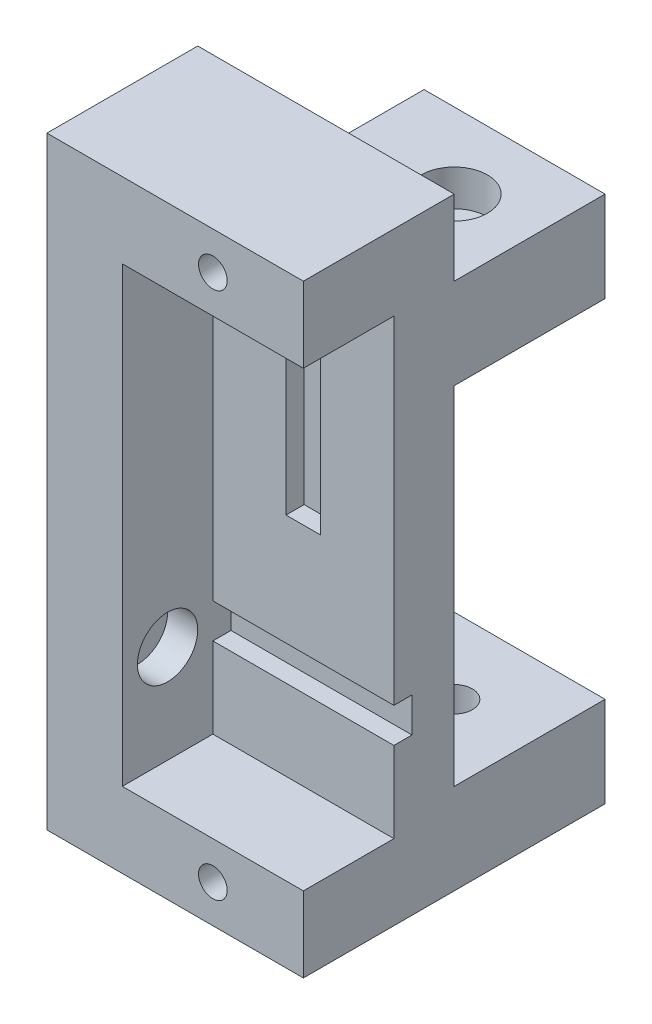
SolidWorks part; units mm, degrees
ref_plane "Plan de face" through (0, 0, 0) normal (0, 0, 1) x (1, 0, 0)
ref_plane "Plan de dessus" through (0, 0, 0) normal (0, 1, 0) x (1, 0, 0)
ref_plane "Plan de droite" through (0, 0, 0) normal (1, 0, 0) x (0, 0, -1)
sketch "Esquisse1" plane through (0, 0, 0) normal (0, 0, 1) x (1, 0, 0)
  line L0 (10, 9.5) -> (10, -9.5) construction
  line L1 (-2, -17.5) -> (10, -17.5)
  line L2 (-2, -17.5) -> (-2, 22.5)
  line L3 (-2, 22.5) -> (10, 22.5)
  line L4 (10, -17.5) -> (10, 22.5)
  line L7 (18, 11.5) -> (0, 11.5) construction
  line L8 (18, -11.5) -> (0, -11.5) construction
  line L9 (0, 11.5) -> (0, -11.5) construction
  dimension "D1" = 11
  dimension "D2" = 6
  dimension "D3" = 2
extrude "Boss.-Extru.1" add sketch "Esquisse1" along normal blind 4
sketch "Esquisse2" plane through (0, 0, 0) normal (0, 0, -1) x (-1, 0, 0)
  line L0 (-10, -17.5) -> (-10, 22.5) construction
  line L1 (2, -17.5) -> (-10, -17.5)
  line L2 (2, -17.5) -> (2, -11.5)
  line L3 (2, -11.5) -> (-10, -11.5)
  line L4 (-10, -17.5) -> (-10, -11.5)
  line L5 (-10, -11.5) -> (0, -11.5) construction
extrude "Boss.-Extru.2" add sketch "Esquisse2" along normal blind 10
mirror "Symétrie1" about plane through (0, 0, 0) normal (0, 1, 0) of "Boss.-Extru.2"
sketch "Esquisse4" plane through (0, 0, 4) normal (0, 0, 1) x (1, 0, 0)
  line L0 (10, -17.5) -> (10, 22.5) construction
  line L1 (-2, 22.5) -> (10, 22.5)
  line L2 (-2, 22.5) -> (-2, 17.5)
  line L3 (-2, 17.5) -> (10, 17.5)
  line L4 (10, 22.5) -> (10, 17.5)
  line L10 (0, 0) -> (3.8663, 0) construction
  line L16 (-2, -17.5) -> (10, -17.5)
  line L17 (-2, -17.5) -> (-2, -12.5)
  line L18 (-2, -12.5) -> (10, -12.5)
  line L19 (10, -17.5) -> (10, -12.5)
  dimension "D1" = 5
extrude "Boss.-Extru.3" add sketch "Esquisse4" along normal blind 6
sketch "Esquisse5" plane through (0, 0, 10) normal (0, 0, 1) x (1, 0, 0)
  line L0 (0, 0) -> (2.5887, 0) construction
  line L1 (-2, -12.5) -> (-2, -17.5) construction
  line L2 (-2, -17.5) -> (10, -17.5) construction
  line L3 (-2, 22.5) -> (-2, 17.5) construction
  line L4 (-2, 17.5) -> (10, 17.5) construction
  circle A0 centre (4, -15) radius 0.95
  circle A1 centre (4, 20) radius 0.95
  point P8 (-2, -15)
  point P11 (4, -17.5)
  point P18 (-2, 20)
  point P21 (4, 17.5)
  dimension "D1" = 1.9
extrude "Enlèv. mat.-Extru.2" cut sketch "Esquisse5" against normal blind 5
sketch "Esquisse6" plane through (-2, 0, 0) normal (-1, 0, 0) x (0, 0, 1)
  line L0 (10, -17.5) -> (-10, -17.5) construction
  line L1 (10, 22.5) -> (0, 22.5)
  line L2 (10, 22.5) -> (10, -17.5)
  line L3 (10, -17.5) -> (0, -17.5)
  line L4 (0, 22.5) -> (0, -17.5)
extrude "Boss.-Extru.4" add sketch "Esquisse6" along normal blind 5
sketch "Esquisse7" plane through (-2, 0, 0) normal (1, 0, 0) x (0, 0, -1)
  line L0 (-4, 17.5) -> (-4, -12.5) construction
  line L2 (-0.66, -6) -> (0.66, -6) construction
  circle A0 centre (-7, -6) radius 2
  point P4 (0, 0)
  point P7 (0, 0)
  point P9 (0, 0)
  point P10 (0, 0)
  dimension "D3" = 4
  dimension "D1" = 3
extrude "Enlèv. mat.-Extru.3" cut sketch "Esquisse7" against normal blind 2
sketch "Esquisse10" plane through (0, -17.5, 0) normal (0, -1, 0) x (-1, 0, 0)
  line L0 (-10, 10) -> (2, 10) construction
  line L1 (-10, -10) -> (-10, 10) construction
  point P0 (-5, 5)
  dimension "D1" = 5
  dimension "D2" = 5
hole_wizard "Chambrage pour vis à six pans creux M21" positions "Esquisse10" profile "Esquisse9" counterbore size "M2" standard "ISO"
sketch "Esquisse9" plane through (5, -17.5, -5) normal (1, 0, 0) x (0, 0, -1)
  line L0 (0, 0) -> (0, 6)
  line L1 (0, 6) -> (1.2, 6)
  line L3 (1.2, 6) -> (1.2, 2.4)
  line L4 (1.2, 2.4) -> (2.2, 2.4)
  line L5 (2.2, 2.4) -> (2.2, 0)
  line L7 (2.2, 0) -> (0, 0)
  line L11 (0, -6.35) -> (0, 107.95) construction
  dimension "Diamètre du perçage jusqu'au prochain" = 2.4
  dimension "Profondeur du perçage jusqu'au prochain" = 6
  dimension "Diamètre du chambrage" = 4.4
  dimension "Profondeur du chambrage" = 2.4
mirror "Symétrie2" about plane through (0, 0, 0) normal (0, 1, 0) of "Chambrage pour vis à six pans creux M21"
sketch "Esquisse15" plane through (0, 0, 4) normal (0, 0, 1) x (1, 0, 0)
  line L0 (-2, -7.15) -> (10, -7.15)
  line L1 (-2, -12.5) -> (-2, 17.5) construction
  line L2 (10, -12.5) -> (10, 17.5) construction
  line L3 (10, -7.15) -> (10, -4.85)
  line L4 (10, -4.85) -> (-2, -4.85)
  line L5 (-2, -4.85) -> (-2, -7.15)
  line L6 (2.85, 17.5) -> (2.85, 2.5)
  line L7 (-2, 17.5) -> (10, 17.5) construction
  line L8 (2.85, 2.5) -> (5.15, 2.5)
  line L9 (5.15, 2.5) -> (5.15, 17.5)
  line L10 (5.15, 17.5) -> (2.85, 17.5)
  line L12 (-0.66, -6) -> (0.66, -6) construction
  line L13 (4, -0.66) -> (4, 0.66) construction
  point P13 (4, 2.5)
  point P15 (-2, -6)
  point P21 (10, -6)
  dimension "D3" = 2.3
  dimension "D5" = 15
extrude "Enlèv. mat.-Extru.4" cut sketch "Esquisse15" against normal blind 1.2
